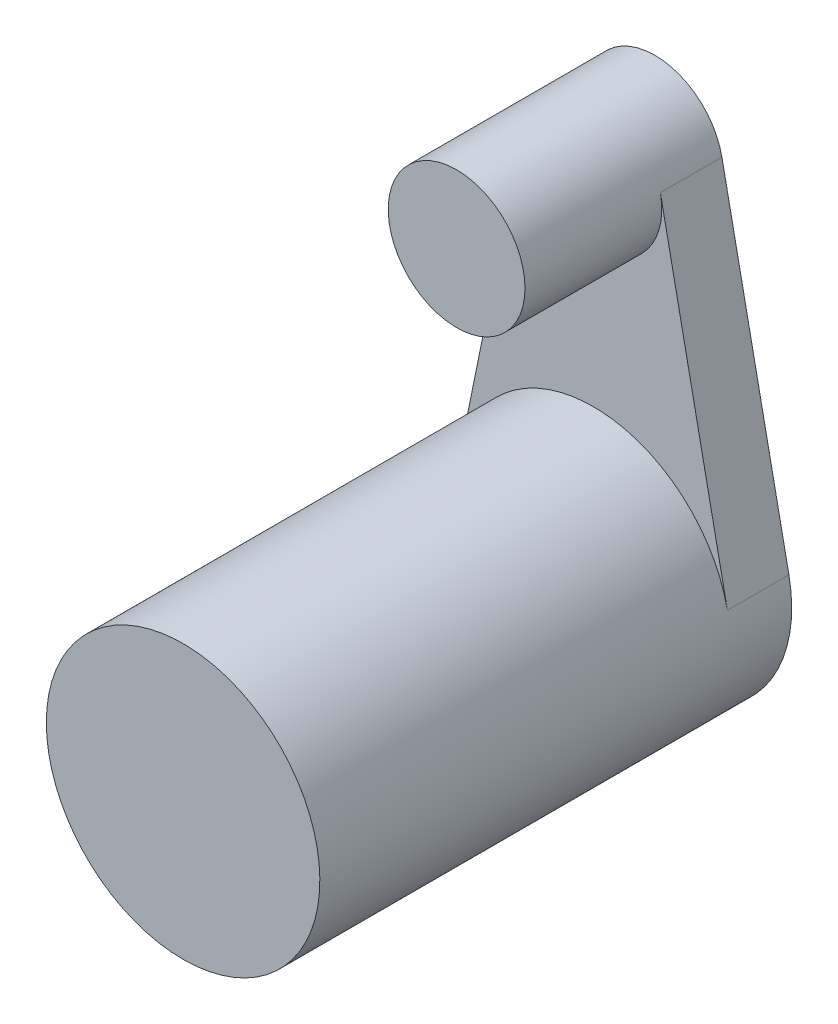
SolidWorks part; units mm, degrees
ref_plane "정면" through (0, 0, 0) normal (0, 0, 1) x (1, 0, 0)
ref_plane "윗면" through (0, 0, 0) normal (0, 1, 0) x (1, 0, 0)
ref_plane "우측면" through (0, 0, 0) normal (1, 0, 0) x (0, 0, -1)
sketch "스케치1" plane through (0, 0, 0) normal (0, 0, 1) x (1, 0, 0)
  circle A0 centre (0, 0) radius 1
  dimension "D1" = 2
extrude "보스-돌출1" add sketch "스케치1" along normal blind 2
sketch "스케치2" plane through (0, 0, 0) normal (0, 0, -1) x (-1, 0, 0)
  circle A0 centre (0, -5) radius 2
  dimension "D1" = 4
  dimension "D2" = 5
extrude "보스-돌출2" add sketch "스케치2" against normal blind 6 separate body
sketch "스케치3" plane through (0, 0, 0) normal (0, 0, -1) x (-1, 0, 0)
  line L0 (0.9798, 0.2) -> (1.9596, -4.6)
  line L1 (-0.9798, 0.2) -> (-1.9596, -4.6)
  circle A0 centre (0, 0) radius 1 construction
  circle A1 centre (0, -5) radius 2 construction
  circle A2 centre (0, 0) radius 1 construction
  circle A3 centre (0, -5) radius 2
  circle A4 centre (0, 0) radius 1
  circle M4 centre (0, 0) radius 1
extrude "보스-돌출3" add sketch "스케치3" along normal blind 0.9 contours M4 | A3 L0 L1 M4 | A3
